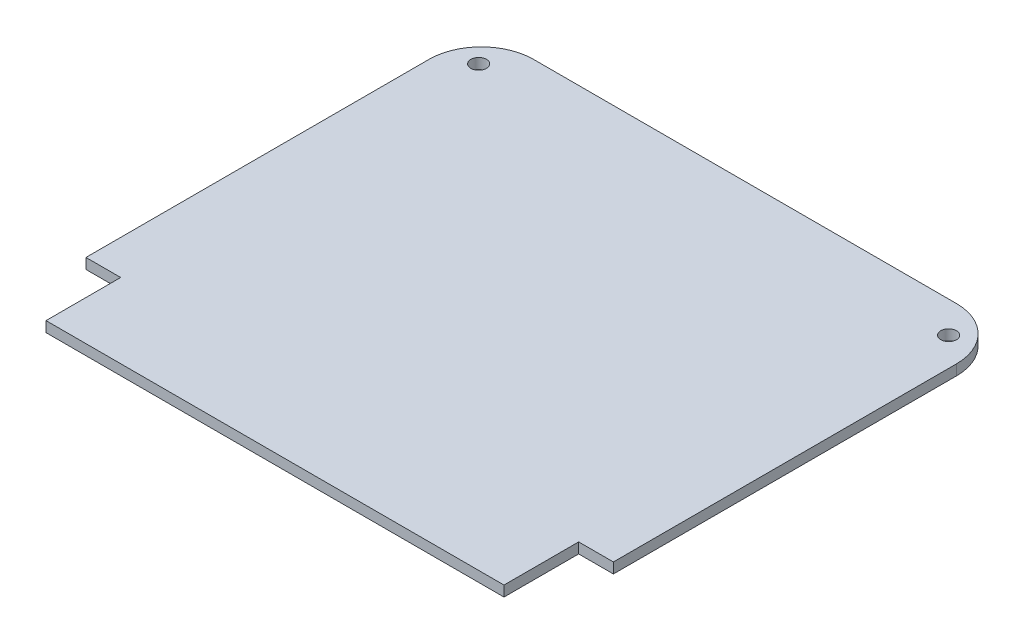
SolidWorks part; units mm, degrees
ref_plane "前视基准面" through (0, 0, 0) normal (0, 0, 1) x (1, 0, 0)
ref_plane "上视基准面" through (0, 0, 0) normal (0, 1, 0) x (1, 0, 0)
ref_plane "右视基准面" through (0, 0, 0) normal (1, 0, 0) x (0, 0, -1)
sketch "草图1" plane through (0, 0, 0) normal (0, 1, 0) x (1, 0, 0)
  line L0 (0, -100.3021) -> (0, -86.0021)
  line L1 (-3.35, -10.3021) -> (-84.35, -10.3021)
  line L2 (-94.35, -20.3021) -> (-94.35, -86.0021)
  line L3 (-94.35, -86.0021) -> (-87.7, -86.0021)
  line L4 (-87.7, -86.0021) -> (-87.7, -100.3021)
  line L5 (-87.7, -100.3021) -> (0, -100.3021)
  line L6 (0, -86.0021) -> (6.65, -86.0021)
  line L7 (6.65, -86.0021) -> (6.65, -20.3021)
  line L8 (-43.85, 85.0959) -> (-43.85, -158.3424) construction
  arc A0 (6.65, -20.3021) -> (-3.35, -10.3021) centre (-3.35, -20.3021) ccw
  arc A1 (-94.35, -20.3021) -> (-84.35, -10.3021) centre (-84.35, -20.3021) cw
  point P11 (-43.85, -100.3021)
  point P12 (-43.85, -10.3021)
  dimension "D4" = 10
  dimension "D1" = 87.7
  dimension "D2" = 101
  dimension "D3" = 14.3
  dimension "D5" = 90
extrude "凸台-拉伸1" add sketch "草图1" along normal blind 2
sketch "草图3" plane through (0, 2, 0) normal (0, 1, 0) x (1, 0, 0)
  line L0 (-43.85, -10.3021) -> (-43.85, -100.3021) construction
  line L1 (-3.35, -10.3021) -> (-84.35, -10.3021) construction
  line L2 (-87.7, -100.3021) -> (0, -100.3021) construction
  line L3 (-88.85, -16.3021) -> (1.15, -16.3021) construction
  circle A0 centre (-88.85, -16.3021) radius 1.5
  circle A1 centre (1.15, -16.3021) radius 1.5
  point P8 (-43.85, -16.3021)
  dimension "D1" = 3
  dimension "D2" = 90
  dimension "D3" = 84
extrude "切除-拉伸1" cut sketch "草图3" against normal blind 10
